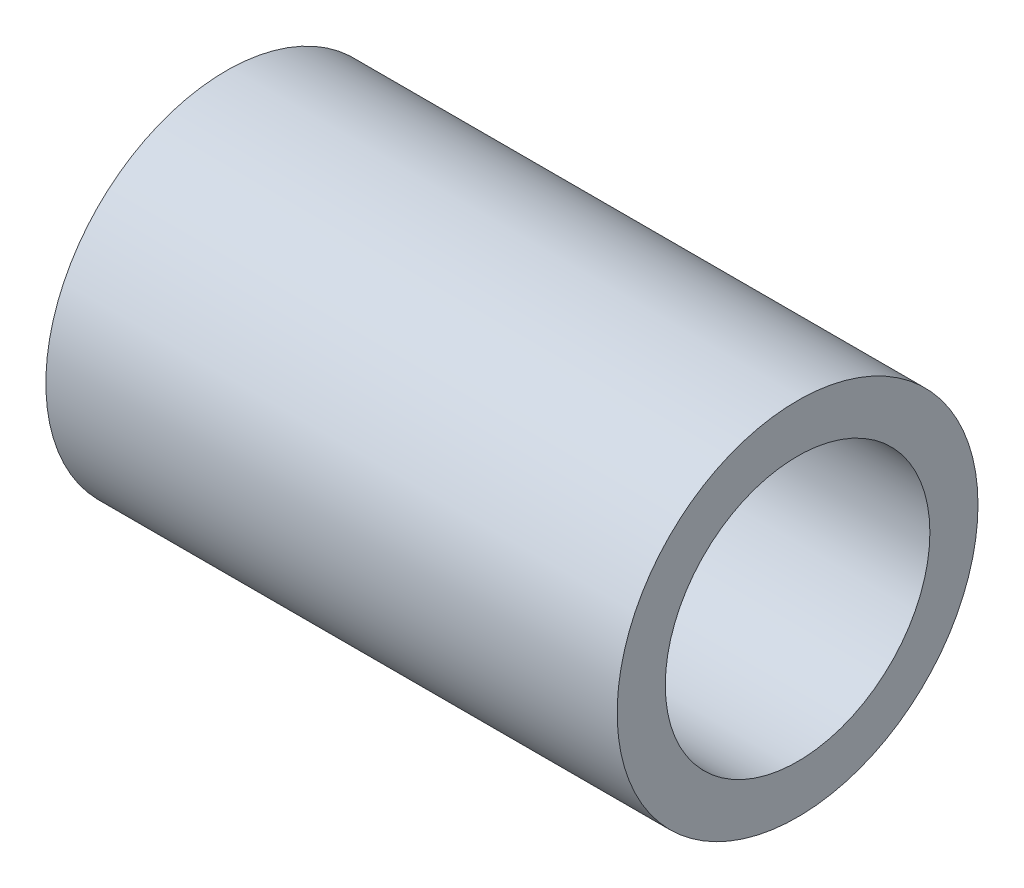
SolidWorks part; units mm, degrees
ref_plane "正面" through (0, 0, 0) normal (0, 0, 1) x (1, 0, 0)
ref_plane "平面" through (0, 0, 0) normal (0, 1, 0) x (1, 0, 0)
ref_plane "右側面" through (0, 0, 0) normal (1, 0, 0) x (0, 0, -1)
sketch "ｽｹｯﾁ1" plane through (0, 0, 0) normal (1, 0, 0) x (0, 0, -1)
  circle A0 centre (-38.7574, 27.3004) radius 2.2
  circle A1 centre (-38.7574, 27.3004) radius 3
extrude "ﾎﾞｽ - 押し出し1" add sketch "ｽｹｯﾁ1" along normal blind 9.5
